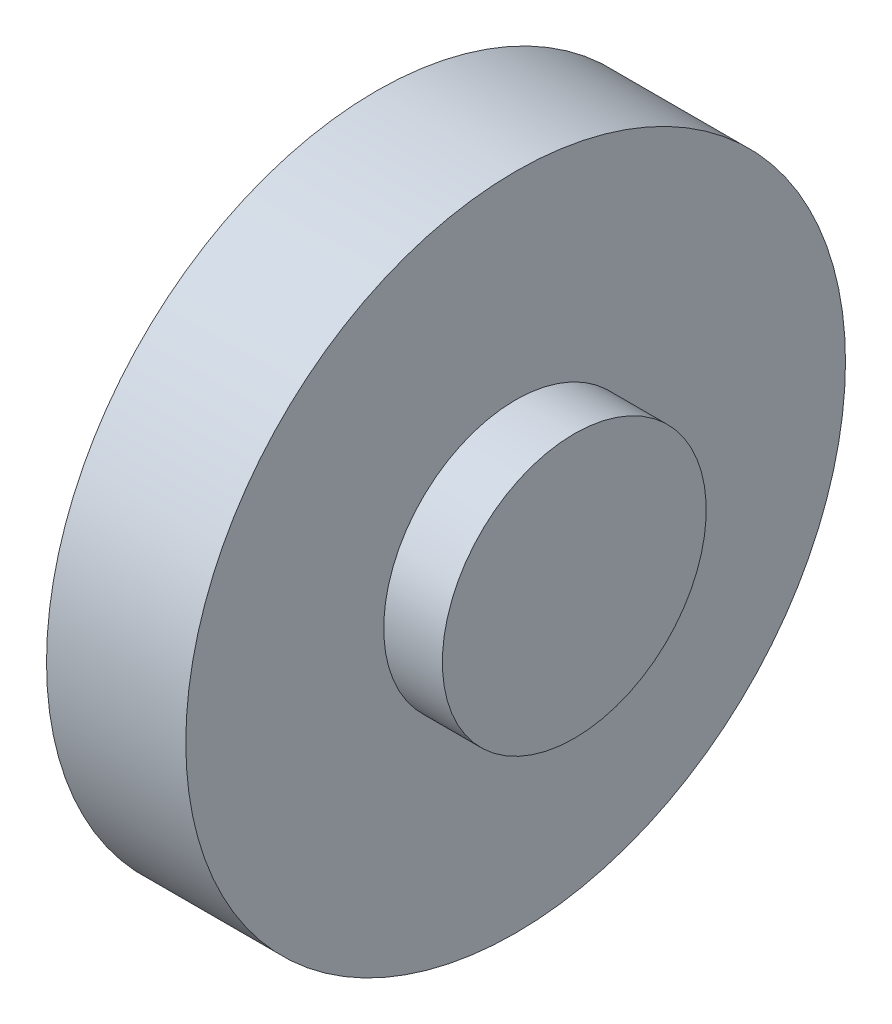
SolidWorks part; units mm, degrees
ref_plane "Front Plane" through (0, 0, 0) normal (0, 0, 1) x (1, 0, 0)
ref_plane "Top Plane" through (0, 0, 0) normal (0, 1, 0) x (1, 0, 0)
ref_plane "Right Plane" through (0, 0, 0) normal (1, 0, 0) x (0, 0, -1)
sketch "Sketch2" plane through (0, 0, 0) normal (0, 0, 1) x (1, 0, 0)
  line L0 (-78.8779, 0) -> (0, 0) construction
  line L1 (0, 0) -> (0, 10)
  line L2 (0, 10) -> (10, 10)
  line L3 (10, 10) -> (10, 45)
  line L4 (10, 45) -> (29, 45)
  line L5 (29, 45) -> (29, 18)
  line L9 (29, 18) -> (37, 18)
  line L10 (37, 18) -> (37, 0)
  line L11 (37, 0) -> (0, 0)
  line L12 (0, 0) -> (78.8779, 0) construction
  dimension "D1" = 20
  dimension "D2" = 90
  dimension "D3" = 19
  dimension "D4" = 10
  dimension "D5" = 8
  dimension "D6" = 36
revolve "Revolve1" add sketch "Sketch2" angle 360 about L0
